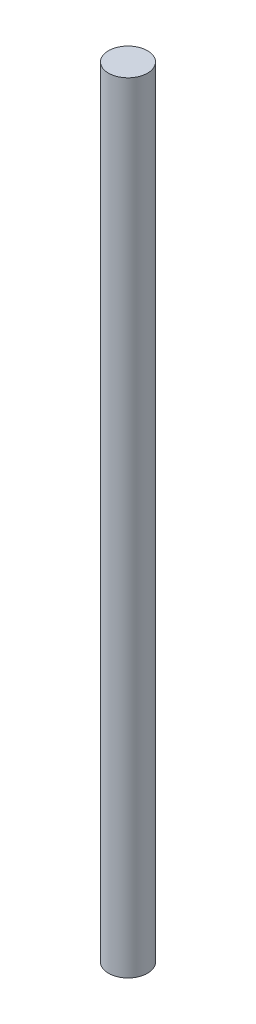
SolidWorks part; units mm, degrees
ref_plane "Płaszczyzna przednia" through (0, 0, 0) normal (0, 0, 1) x (1, 0, 0)
ref_plane "Płaszczyzna górna" through (0, 0, 0) normal (0, 1, 0) x (1, 0, 0)
ref_plane "Płaszczyzna prawa" through (0, 0, 0) normal (1, 0, 0) x (0, 0, -1)
sketch "Szkic1" plane through (0, 0, 0) normal (0, 1, 0) x (1, 0, 0)
  circle A0 centre (0, 0) radius 0.5
  dimension "D1" = 1
extrude "Dodanie-wyciągnięcie1" add sketch "Szkic1" along normal blind 20
